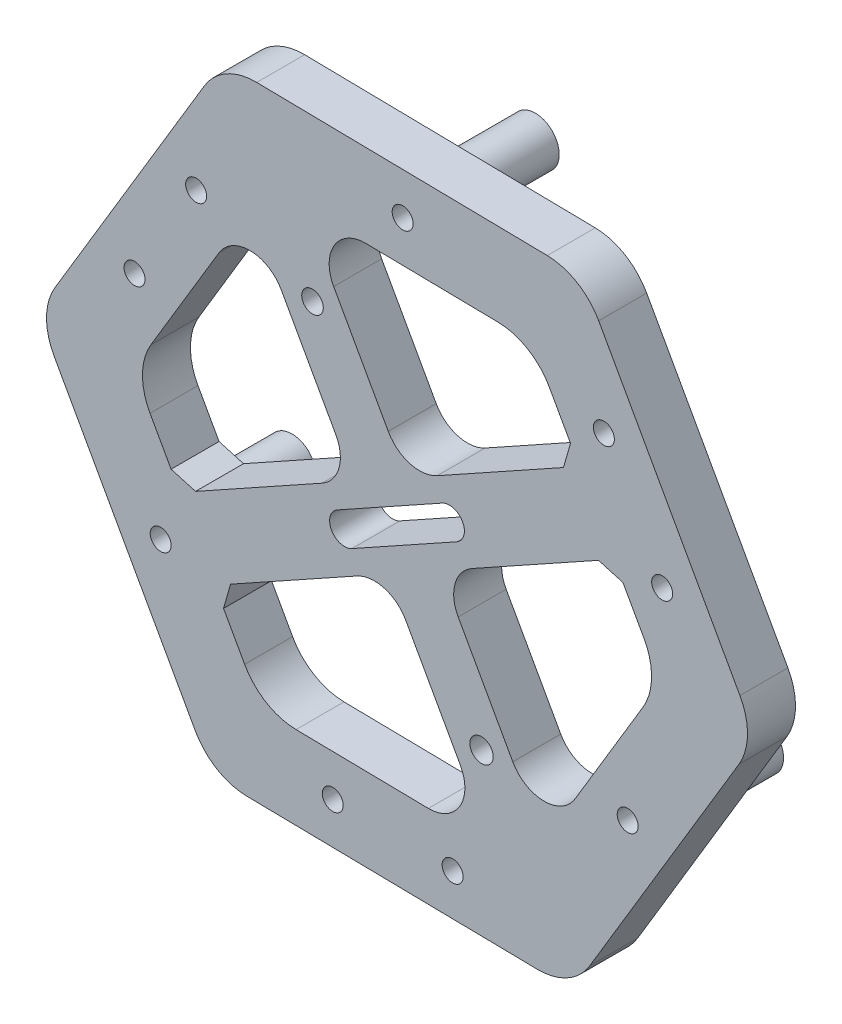
SolidWorks part; units mm, degrees
ref_plane "Front Plane" through (0, 0, 0) normal (0, 0, 1) x (1, 0, 0)
ref_plane "Top Plane" through (0, 0, 0) normal (0, 1, 0) x (1, 0, 0)
ref_plane "Right Plane" through (0, 0, 0) normal (1, 0, 0) x (0, 0, -1)
sketch "Sketch1" plane through (0, 0, 0) normal (0, 0, 1) x (1, 0, 0)
  line L1 (30.8332, 51.4805) -> (-29.1668, 52.4426)
  line L2 (-29.1668, 52.4426) -> (-60, 0.9621)
  line L3 (-60, 0.9621) -> (-30.8332, -51.4805)
  line L4 (-30.8332, -51.4805) -> (29.1668, -52.4426)
  line L5 (29.1668, -52.4426) -> (60, -0.9621)
  line L6 (60, -0.9621) -> (30.8332, 51.4805)
  circle A0 centre (0, 0) radius 51.9682 construction
  dimension "D1" = 60
extrude "Boss-Extrude1" add sketch "Sketch1" along normal blind 8
sketch "Sketch2" plane through (0, 0, 8) normal (0, 0, 1) x (1, 0, 0)
  line L0 (30.8332, 51.4805) -> (-29.1668, 52.4426) construction
  line L1 (-21.389, 38.4579) -> (-44, 0.7056)
  line L2 (-44, 0.7056) -> (-22.611, -37.7523)
  line L3 (-22.611, -37.7523) -> (21.389, -38.4579)
  line L4 (21.389, -38.4579) -> (44, -0.7056)
  line L5 (44, -0.7056) -> (22.611, 37.7523)
  line L6 (22.611, 37.7523) -> (-21.389, 38.4579)
  circle A0 centre (0, 0) radius 38.11 construction
  dimension "D1" = 44
extrude "Cut-Extrude1" cut sketch "Sketch2" against normal blind 10
sketch "Sketch3" plane through (0, 0, 0) normal (0, 0, -1) x (-1, 0, 0)
  line L0 (0.8332, -51.9615) -> (0, 0) construction
  line L1 (30.8332, -51.4805) -> (-29.1668, -52.4426) construction
  line L2 (0.8332, -51.9615) -> (0.611, -38.1051) construction
  line L3 (22.611, -37.7523) -> (-21.389, -38.4579) construction
  circle A0 centre (-9.2766, -45.1927) radius 1.75
  circle A6 centre (10.7208, -44.8721) radius 1.75
  circle A7 centre (-34.4998, 30.6301) radius 1.75
  circle A8 centre (-44.2208, 13.1515) radius 1.75
  circle A9 centre (43.7764, 14.5626) radius 1.75
  circle A10 centre (33.5, 31.7205) radius 1.75
  point P22 (0, 0)
  dimension "D2" = 3.5
  dimension "D1" = 10
  dimension "D3" = 6.93
  dimension "D4" = 3
extrude "Cut-Extrude2" cut sketch "Sketch3" against normal blind 10
fillet "Fillet1" radius 10 12 edges at (-29.1668, 52.4426, 4) (30.8332, 51.4805, 4) (60, -0.9621, 4) (29.1668, -52.4426, 4) (-30.8332, -51.4805, 4) (-60, 0.9621, 4) (44, -0.7056, 4) (21.389, -38.4579, 4) (-22.611, -37.7523, 4) (-44, 0.7056, 4) (-21.389, 38.4579, 4) (22.611, 37.7523, 4)
sketch "Sketch4" plane through (0, 0, 0) normal (0, 0, -1) x (-1, 0, 0)
  line L0 (-33.3055, 18.5234) -> (33.3055, -18.5234) construction
  line L1 (-41.1938, 4.3401) -> (-25.4172, 32.7067) construction
  line L2 (41.1938, -4.3401) -> (25.4172, -32.7067) construction
  line L3 (-30.3892, 23.767) -> (36.2218, -13.2798)
  line L4 (-36.2218, 13.2798) -> (-30.3892, 23.767)
  line L5 (30.3892, -23.767) -> (36.2218, -13.2798)
  line L6 (-36.2218, 13.2798) -> (30.3892, -23.767)
  dimension "D1" = 6
extrude "Boss-Extrude2" add sketch "Sketch4" against normal up to surface (8 mm away) up to face at (-42.0264, 14.5626, 8)
chamfer "Chamfer1" distance 3 angle 45 4 edges at (-30.3892, -23.767, 4) (-36.2218, -13.2798, 4) (30.3892, 23.767, 4) (36.2218, 13.2798, 4)
sketch "Sketch5" plane through (0, 0, 0) normal (0, 0, -1) x (-1, 0, 0)
  circle A0 centre (43.7764, 14.5626) radius 3.1
  circle A1 centre (33.5, 31.7205) radius 3.1
  circle A2 centre (-9.2766, -45.1927) radius 3.1
  circle A3 centre (10.7208, -44.8721) radius 3.1
  circle A4 centre (-34.4998, 30.6301) radius 3.1
  circle A5 centre (-44.2208, 13.1515) radius 3.1
  point P17 (0, 0)
  dimension "D1" = 6.2
  dimension "D2" = 6.2
  dimension "D3" = 3
extrude "Cut-Extrude3" cut sketch "Sketch5" against normal blind 4
sketch "Sketch7" plane through (0, 0, 0) normal (0, 0, -1) x (-1, 0, 0)
  line L0 (0, 0) -> (9.7673, 17.5618) construction
  line L1 (33.6, -11.8217) -> (-27.7674, 22.3088) construction
  line L2 (-1.4534, 7.6738) -> (20.4189, 47.0007)
  line L3 (20.4189, 47.0007) -> (29.1582, 42.1402)
  line L4 (-1.4534, 7.6738) -> (7.286, 2.8133)
  line L5 (7.286, 2.8133) -> (29.1582, 42.1402)
  line L6 (0, 0) -> (-18.408, 10.2379) construction
  line L7 (1.4534, -7.6738) -> (-20.4189, -47.0007)
  line L8 (-7.286, -2.8133) -> (1.4534, -7.6738)
  line L9 (-29.1582, -42.1402) -> (-20.4189, -47.0007)
  line L10 (-7.286, -2.8133) -> (-29.1582, -42.1402)
  point P10 (24.7886, 44.5705)
  point P11 (2.9163, 5.2436)
  point P16 (-2.9163, -5.2436)
  point P17 (-24.7886, -44.5705)
  dimension "D1" = 45
  dimension "D2" = 10
extrude "Boss-Extrude3" add sketch "Sketch7" against normal up to surface (8 mm away) up to face at (9.5827, -17.23, 8)
sketch "Sketch9" plane through (0, 0, 0) normal (0, 0, -1) x (-1, 0, 0)
  line L0 (25.4172, -32.7067) -> (37.9891, -38.6141) construction
  line L1 (57.1938, -4.0835) -> (33.6394, -46.4348) construction
  line L2 (41.1938, -4.3401) -> (53.7236, -10.3229) construction
  line L3 (31.5817, -35.6251) -> (47.4587, -7.3315) construction
  circle A0 centre (39.5202, -21.4783) radius 4
  circle A2 centre (-38.4715, -23.3016) radius 4
  circle A3 centre (-1.0546, 45.1529) radius 4
  point P18 (-0.002, 0.1243)
  dimension "D1" = 8
  dimension "D2" = 3
extrude "Boss-Extrude5" add sketch "Sketch9" along normal blind 14
sketch "Sketch10" plane through (0, 0, -14) normal (0, 0, -1) x (-1, 0, 0)
  circle A0 centre (-38.4715, -23.3016) radius 1.75
  circle A1 centre (-0.944, 44.9681) radius 1.75
  circle A2 centre (39.4155, -21.6665) radius 1.75
  point P10 (0, 0)
  dimension "D1" = 3.5
  dimension "D2" = 3
extrude "Cut-Extrude4" cut sketch "Sketch10" against normal blind 37
fillet "Fillet4" radius 1 3 edges at (-35.5202, -21.4783, 0) (5.0546, 45.1529, 0) (42.4715, -23.3016, 0)
sketch "Sketch11" plane through (0, 0, 0) normal (0, 0, -1) x (-1, 0, 0)
  line L0 (-45.4166, 25.2592) -> (45.4166, -25.2592) construction
  line L1 (-57.1938, 4.0835) -> (-33.6394, 46.4348) construction
  line L2 (57.1938, -4.0835) -> (33.6394, -46.4348) construction
  line L3 (-8.7393, 4.8605) -> (8.7393, -4.8605) construction
  line L4 (-7.5242, 7.0453) -> (9.9544, -2.6757)
  line L5 (-9.9544, 2.6757) -> (7.5242, -7.0453)
  arc A0 (-7.5242, 7.0453) -> (-9.9544, 2.6757) centre (-8.7393, 4.8605) ccw
  arc A1 (7.5242, -7.0453) -> (9.9544, -2.6757) centre (8.7393, -4.8605) ccw
  point P8 (0, 0)
  dimension "D1" = 20
  dimension "D2" = 5
extrude "Cut-Extrude5" cut sketch "Sketch11" against normal blind 10
ref_plane "Plane1" through (0, 0, 0) normal (-0.8739, -0.4861, 0) x (0, 0, 1)
fillet "Fillet9" radius 6 4 edges at (-15.6162, 38.3653, 4) (-24.3555, 33.5048, 4) (24.3555, -33.5048, 4) (15.6162, -38.3653, 4)
fillet "Fillet10" radius 6 4 edges at (1.4534, 7.6738, 4) (-7.286, 2.8133, 4) (-1.4534, -7.6738, 4) (7.286, -2.8133, 4)
sketch "Sketch13" plane through (0, 0, 0) normal (0, 0, -1) x (-1, 0, 0)
  circle A0 centre (-14.0947, -25.3426) radius 1.9486
  circle A1 centre (14.0962, 25.3454) radius 1.8
extrude "Cut-Extrude7" cut sketch "Sketch13" against normal blind 22
